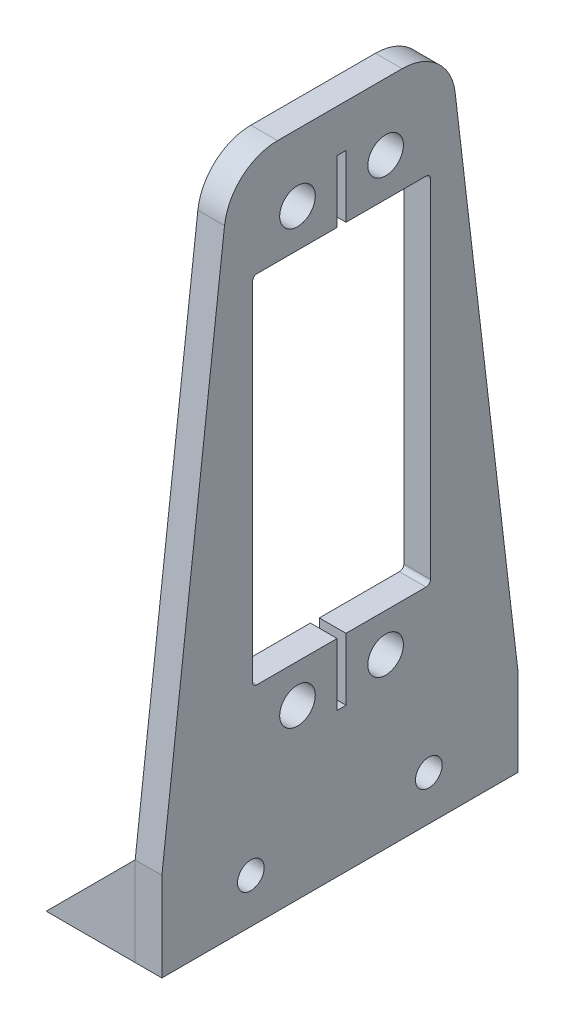
SolidWorks part; units mm, degrees
ref_plane "Front Plane" through (0, 0, 0) normal (0, 0, 1) x (1, 0, 0)
ref_plane "Top Plane" through (0, 0, 0) normal (0, 1, 0) x (1, 0, 0)
ref_plane "Right Plane" through (0, 0, 0) normal (1, 0, 0) x (0, 0, -1)
sketch "Sketch1" plane through (0, 0, 0) normal (0, 0, 1) x (1, 0, 0)
  line L4 (0, 0) -> (20, 0) construction
  line L5 (20, 0) -> (20, 10)
  line L6 (20, 10) -> (10, 0)
  line L7 (10, 0) -> (20, 0)
  point P4 (34.2542, 10)
  dimension "D1" = 45
  dimension "D2" = 10
  dimension "D3" = 20
extrude "Boss-Extrude1" add sketch "Sketch1" along normal mid plane 40
sketch "Sketch3" plane through (0, 0, 0) normal (1, 0, 0) x (0, 0, -1)
  line B0 (9.0915, 57.5) -> (-8.7085, 57.5)
  line B1 (-8.7085, 57.5) -> (-8.7085, 44.8)
  line B2 (9.0915, 44.8) -> (9.0915, 57.5)
  line B3 (-10.0585, 63.2) -> (-10.0585, 23.2)
  line B4 (-9.0585, 23.2) -> (-9.3085, 23.2)
  line B5 (-9.8085, 23.7) -> (-9.8085, 62.7)
  line B6 (-9.3085, 63.2) -> (-9.0585, 63.2)
  line B7 (-9.0585, 63.2) -> (-9.0585, 63.7)
  line B8 (-0.3085, 70.2) -> (-0.3085, 63.2)
  line B9 (-0.3085, 63.2) -> (0.6915, 63.2)
  line B10 (0.6915, 63.2) -> (0.6915, 70.2)
  line B11 (0.6915, 70.2) -> (-0.3085, 70.2)
  line B12 (-9.0585, 63.2) -> (-0.3085, 63.2)
  line B13 (0.6915, 63.2) -> (9.4415, 63.2)
  line B14 (9.4415, 63.2) -> (9.4415, 68.7)
  line B15 (3.6415, 70.2) -> (0.6915, 70.2)
  line B16 (10.4415, 23.2) -> (10.4415, 63.2)
  line B17 (9.4415, 63.2) -> (9.6915, 63.2)
  line B18 (10.1915, 62.7) -> (10.1915, 23.7)
  line B19 (9.6915, 23.2) -> (9.4415, 23.2)
  line B20 (9.4415, 23.2) -> (9.4415, 22.7)
  line B21 (-0.3085, 23.2) -> (-0.3085, 16.2)
  line B22 (-0.3085, 16.2) -> (0.6915, 16.2)
  line B23 (0.6915, 16.2) -> (0.6915, 23.2)
  line B24 (0.6915, 23.2) -> (-0.3085, 23.2)
  line B25 (4.1415, 16.7) -> (4.1415, 17.1679)
  line B26 (6.1415, 17.1679) -> (6.1415, 16.7)
  line B27 (9.4415, 17.7) -> (9.4415, 23.2)
  line B28 (9.4415, 23.2) -> (0.6915, 23.2)
  line B29 (-0.3085, 23.2) -> (-9.0585, 23.2)
  line B30 (-9.0585, 23.2) -> (-9.0585, 17.7)
  circle B31 centre (0.1915, 33) radius 5.3
  arc B32 (-8.7085, 36.9815) -> (9.0915, 36.9815) centre (0.1915, 33) ccw
  arc B33 (5.3239, 57.5) -> (-4.9409, 57.5) centre (0.1915, 53.8069) ccw
  arc B34 (-9.8085, 23.7) -> (-9.3085, 23.2) centre (-9.3085, 23.7) ccw
  arc B35 (-9.3085, 63.2) -> (-9.8085, 62.7) centre (-9.3085, 62.7) ccw
  arc B36 (-5.7585, 69.2321) -> (-3.7585, 69.2321) centre (-4.7585, 67.5) ccw
  arc B37 (4.1415, 69.2321) -> (6.1415, 69.2321) centre (5.1415, 67.5) ccw
  arc B38 (10.1915, 62.7) -> (9.6915, 63.2) centre (9.6915, 62.7) ccw
  arc B39 (9.6915, 23.2) -> (10.1915, 23.7) centre (9.6915, 23.7) ccw
  arc B40 (3.6415, 16.2) -> (4.1415, 16.7) centre (3.6415, 16.7) ccw
  arc B41 (6.1415, 17.1679) -> (4.1415, 17.1679) centre (5.1415, 18.9) ccw
  arc B42 (7.9415, 16.2) -> (9.4415, 17.7) centre (7.9415, 17.7) ccw
  arc B43 (-3.7585, 17.1679) -> (-5.7585, 17.1679) centre (-4.7585, 18.9) ccw
  dimension "D1" = 33
sketch_block_instance "servo 996 top-1"
sketch_block "servo 996 top"
sketch "Sketch2" plane through (20, 0, 0) normal (1, 0, 0) x (0, 0, -1)
  line L0 (0, 0) -> (0, 75) construction
  line L1 (20, 10) -> (12.9587, 69.7028)
  line L2 (-20, 10) -> (-12.9587, 69.7028)
  line L3 (7, 75) -> (-7, 75)
  line L4 (20, 0) -> (20, 10)
  line L5 (20, 10) -> (-20, 10)
  line L6 (-20, 10) -> (-20, 0)
  line L7 (-20, 0) -> (20, 0)
  line L8 (20, 0) -> (20, 10)
  line L10 (-20, 10) -> (-20, 0)
  line L11 (-20, 0) -> (20, 0)
  arc A1 (-12.9587, 69.7028) -> (-7, 75) centre (-7, 69) cw
  arc A2 (12.9587, 69.7028) -> (7, 75) centre (7, 69) ccw
  point P6 (0, 75)
  dimension "D2" = 6
  dimension "D3" = 75
  dimension "D4" = 14
  dimension "D1" = 0
extrude "Boss-Extrude2" add sketch "Sketch2" along normal blind 3 separate body
sketch "Sketch4" plane through (23, 0, 0) normal (1, 0, 0) x (0, 0, -1)
  line L0 (-0.3085, 23.2) -> (-0.3085, 16.2) construction
  line L1 (-0.3085, 16.2) -> (0.6915, 16.2) construction
  line L2 (0.6915, 16.2) -> (0.6915, 23.2) construction
  line L3 (-0.3085, 70.2) -> (-0.3085, 63.2) construction
  line L4 (0.6915, 70.2) -> (-0.3085, 70.2) construction
  line L5 (0.6915, 63.2) -> (0.6915, 70.2) construction
  line L6 (-9.3085, 63.2) -> (-9.0585, 63.2) construction
  line L7 (-9.8085, 23.7) -> (-9.8085, 62.7) construction
  line L8 (-9.0585, 23.2) -> (-9.3085, 23.2) construction
  line L9 (-0.3085, 23.2) -> (-9.0585, 23.2) construction
  line L11 (9.4415, 23.2) -> (0.6915, 23.2) construction
  line L12 (9.6915, 23.2) -> (9.4415, 23.2) construction
  line L13 (10.1915, 62.7) -> (10.1915, 23.7) construction
  line L14 (9.4415, 63.2) -> (9.6915, 63.2) construction
  line L15 (0.6915, 63.2) -> (9.4415, 63.2) construction
  line L17 (-9.0585, 63.2) -> (-0.3085, 63.2) construction
  line L18 (-0.3085, 23.2) -> (-0.3085, 16.2)
  line L19 (-0.3085, 16.2) -> (0.6915, 16.2)
  line L20 (0.6915, 16.2) -> (0.6915, 23.2)
  line L21 (-0.3085, 70.2) -> (-0.3085, 63.2)
  line L22 (0.6915, 70.2) -> (-0.3085, 70.2)
  line L23 (0.6915, 63.2) -> (0.6915, 70.2)
  line L24 (-9.3085, 63.2) -> (-9.0585, 63.2)
  line L25 (-9.8085, 23.7) -> (-9.8085, 62.7)
  line L26 (-9.0585, 23.2) -> (-9.3085, 23.2)
  line L27 (-0.3085, 23.2) -> (-9.0585, 23.2)
  line L29 (9.4415, 23.2) -> (0.6915, 23.2)
  line L30 (9.6915, 23.2) -> (9.4415, 23.2)
  line L31 (10.1915, 62.7) -> (10.1915, 23.7)
  line L32 (9.4415, 63.2) -> (9.6915, 63.2)
  line L33 (0.6915, 63.2) -> (9.4415, 63.2)
  line L35 (-9.0585, 63.2) -> (-0.3085, 63.2)
  arc A4 (-9.3085, 63.2) -> (-9.8085, 62.7) centre (-9.3085, 62.7) ccw construction
  arc A5 (-9.8085, 23.7) -> (-9.3085, 23.2) centre (-9.3085, 23.7) ccw construction
  arc A6 (9.6915, 23.2) -> (10.1915, 23.7) centre (9.6915, 23.7) ccw construction
  arc A7 (10.1915, 62.7) -> (9.6915, 63.2) centre (9.6915, 62.7) ccw construction
  circle A8 centre (5.1415, 67.5) radius 2
  circle A9 centre (-4.7585, 67.5) radius 2
  circle A10 centre (5.1415, 18.9) radius 2
  circle A11 centre (-4.7585, 18.9) radius 2
  arc A12 (-9.3085, 63.2) -> (-9.8085, 62.7) centre (-9.3085, 62.7) ccw
  arc A13 (-9.8085, 23.7) -> (-9.3085, 23.2) centre (-9.3085, 23.7) ccw
  arc A14 (9.6915, 23.2) -> (10.1915, 23.7) centre (9.6915, 23.7) ccw
  arc A15 (10.1915, 62.7) -> (9.6915, 63.2) centre (9.6915, 62.7) ccw
  arc A16 (6.1415, 17.1679) -> (4.1415, 17.1679) centre (5.1415, 18.9) ccw construction
  arc A17 (-3.7585, 17.1679) -> (-5.7585, 17.1679) centre (-4.7585, 18.9) ccw construction
extrude "Cut-Extrude1" cut sketch "Sketch4" against normal up to next (3 mm away)
sketch "Sketch5" plane through (23, 0, 0) normal (1, 0, 0) x (0, 0, -1)
  line L0 (20, 5) -> (-20, 5) construction
  line L1 (20, 0) -> (20, 10) construction
  line L2 (-20, 10) -> (-20, 0) construction
  line L3 (-10, 5) -> (10, 5) construction
  circle A0 centre (10, 5) radius 1.5
  circle A1 centre (-10, 5) radius 1.5
  point P10 (0, 0)
  point P13 (0, 5)
  point P14 (0, 0)
  dimension "D2" = 3
  dimension "D1" = 20
extrude "Cut-Extrude2" cut sketch "Sketch5" against normal up to next (3 mm away)
